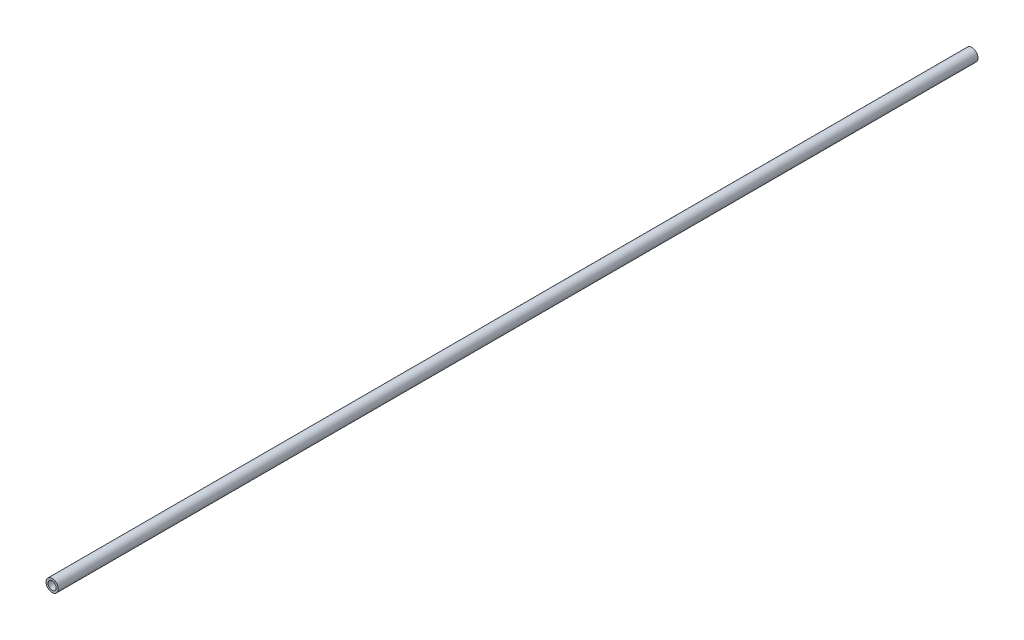
SolidWorks part; units mm, degrees
ref_plane "Plano frontal" through (0, 0, 0) normal (0, 0, 1) x (1, 0, 0)
ref_plane "Plano superior" through (0, 0, 0) normal (0, 1, 0) x (1, 0, 0)
ref_plane "Plano direito" through (0, 0, 0) normal (1, 0, 0) x (0, 0, -1)
sketch "Esboço1" plane through (0, 0, 0) normal (0, 0, 1) x (1, 0, 0)
  circle A0 centre (0, 0) radius 3
  circle A1 centre (0, 0) radius 2
  dimension "D1" = 6
extrude "Ressalto-extrusão1" add sketch "Esboço1" along normal blind 450
